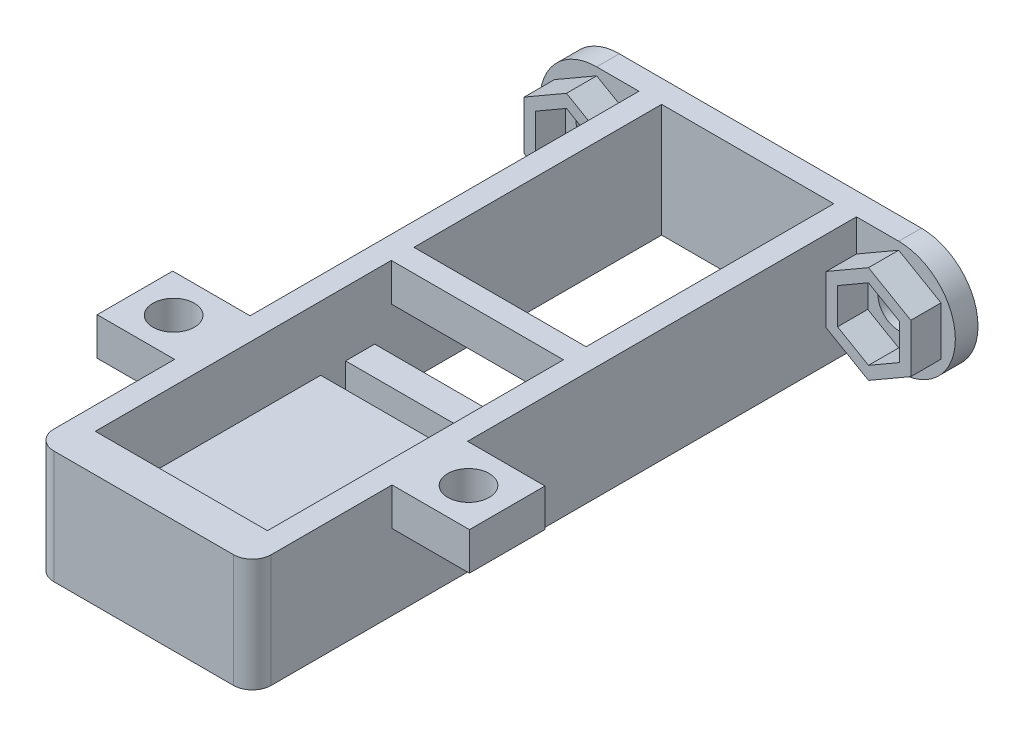
SolidWorks part; units mm, degrees
ref_plane "Front Plane" through (0, 0, 0) normal (0, 0, 1) x (1, 0, 0)
ref_plane "Top Plane" through (0, 0, 0) normal (0, 1, 0) x (1, 0, 0)
ref_plane "Right Plane" through (0, 0, 0) normal (1, 0, 0) x (0, 0, -1)
sketch "Sketch2" plane through (0, 0, 0) normal (0, 0, 1) x (1, 0, 0)
  line L0 (-20, -22.5) -> (20, -22.5)
  line L1 (20, -37.5) -> (-20, -37.5)
  line L3 (12.5, -30) -> (12.5, -22.5)
  circle A0 centre (20, -30) radius 2.75 construction
  circle A1 centre (-20, -30) radius 2.75 construction
  circle A2 centre (20, -30) radius 2.75
  circle A3 centre (-20, -30) radius 2.75
  circle A4 centre (-20, -30) radius 7.5
  circle A5 centre (20, -30) radius 7.5
  circle M2 centre (20, -30) radius 2.75
  circle M15 centre (-20, -30) radius 2.75
  dimension "D1" = 15
  dimension "D2" = 15
extrude "Boss-Extrude1" add sketch "Sketch2" along normal blind 3 contours A4 M15 | A5 L3 L0 A4 L1 | A5 M2 | A5 L0 L3
sketch "Sketch3" plane through (0, 0, 3) normal (0, 0, 1) x (1, 0, 0)
  line L0 (-20, -23.5337) -> (-25.6, -26.7668)
  line L1 (-20, -25.2657) -> (-24.1, -27.6329)
  line L2 (-24.1, -27.6329) -> (-24.1, -32.3671)
  line L3 (-24.1, -32.3671) -> (-20, -34.7343)
  line L4 (-20, -34.7343) -> (-15.9, -32.3671)
  line L5 (-15.9, -32.3671) -> (-15.9, -27.6329)
  line L6 (-15.9, -27.6329) -> (-20, -25.2657)
  line L7 (20, -25.2657) -> (15.9, -27.6329)
  line L8 (15.9, -27.6329) -> (15.9, -32.3671)
  line L9 (15.9, -32.3671) -> (20, -34.7343)
  line L10 (20, -34.7343) -> (24.1, -32.3671)
  line L11 (24.1, -32.3671) -> (24.1, -27.6329)
  line L12 (24.1, -27.6329) -> (20, -25.2657)
  line L13 (-25.6, -26.7668) -> (-25.6, -33.2332)
  line L14 (-25.6, -33.2332) -> (-20, -36.4663)
  line L15 (-20, -36.4663) -> (-14.4, -33.2332)
  line L16 (-14.4, -33.2332) -> (-14.4, -26.7668)
  line L17 (-14.4, -26.7668) -> (-20, -23.5337)
  line L18 (20, -23.5337) -> (14.4, -26.7668)
  line L19 (14.4, -26.7668) -> (14.4, -33.2332)
  line L20 (14.4, -33.2332) -> (20, -36.4663)
  line L21 (20, -36.4663) -> (25.6, -33.2332)
  line L22 (25.6, -33.2332) -> (25.6, -26.7668)
  line L23 (25.6, -26.7668) -> (20, -23.5337)
  circle A0 centre (-20, -30) radius 4.1 construction
  circle A1 centre (20, -30) radius 4.1 construction
  circle A2 centre (-20, -30) radius 5.6
  circle A3 centre (20, -30) radius 5.6
  dimension "D1" = 8.2
  dimension "D2" = 8.2
  dimension "D3" = 1.5
extrude "Boss-Extrude2" add sketch "Sketch3" along normal blind 4 contours A2 L16 L17 | A2 L6 L5 L4 L3 L2 L1 | A2 L17 L0 | A2 L0 L13 | A2 L13 L14 | A2 L14 L15 | A2 L15 L16 | A3 L22 L23 | A3 L12 L11 L10 L9 L8 L7 | A3 L23 L18 | A3 L18 L19 | A3 L19 L20 | A3 L20 L21 | A3 L21 L22
sketch "Sketch4" plane through (0, 0, 3) normal (0, 0, 1) x (1, 0, 0)
  line L0 (-14.4, -26.7668) -> (-14.4, -22.5)
  line L1 (-20, -22.5) -> (20, -22.5) construction
  line L2 (-14.4, -22.5) -> (-11.4, -22.5)
  line L3 (-11.4, -22.5) -> (-11.4, -37.5)
  line L4 (20, -37.5) -> (-20, -37.5) construction
  line L5 (-11.4, -37.5) -> (-14.4, -37.5)
  line L6 (-14.4, -37.5) -> (-14.4, -26.7668)
  line L7 (14.4, -30) -> (14.4, -22.5)
  line L8 (14.4, -26.7668) -> (14.4, -33.2332) construction
  line L9 (14.4, -22.5) -> (11.4, -22.5)
  line L10 (11.4, -22.5) -> (11.4, -37.5)
  line L11 (11.4, -37.5) -> (14.4, -37.5)
  line L12 (14.4, -37.5) -> (14.4, -30)
  dimension "D1" = 3
  dimension "D2" = 3
extrude "Boss-Extrude3" add sketch "Sketch4" along normal blind 80
sketch "Sketch5" plane through (11.4, 0, 0) normal (-1, 0, 0) x (0, 0, 1)
  line L0 (78, -31) -> (48.15, -31)
  line L1 (41, -37.5) -> (44.85, -37.5)
  line L2 (83, -37.5) -> (3, -37.5) construction
  line L3 (78, -37.5) -> (3, -37.5)
  line L4 (41, -31) -> (44.85, -31)
  line L5 (48.15, -37.5) -> (78, -37.5)
  line L6 (41, -31) -> (41, -37.5)
  line L7 (78, -31) -> (78, -37.5)
  line L9 (48.15, -37.5) -> (48.15, -31)
  line L11 (44.85, -37.5) -> (44.85, -31)
  line M6 (3, -37.5) -> (83, -37.5)
extrude "Boss-Extrude4" add sketch "Sketch5" along normal blind 80 contours L9 L3 L7 L0 | L11 L4 L6 M6
sketch "Sketch6" plane through (-68.6, 0, 0) normal (-1, 0, 0) x (0, 0, 1)
  line L4 (48.15, -31) -> (48.15, -37.5)
  line L5 (48.15, -37.5) -> (78, -37.5)
  line L6 (78, -37.5) -> (78, -31)
  line L7 (78, -31) -> (48.15, -31)
  line L8 (48.15, -31) -> (48.15, -37.5)
  line L9 (48.15, -37.5) -> (78, -37.5)
  line L10 (78, -37.5) -> (78, -31)
  line L11 (78, -31) -> (48.15, -31)
  line L12 (41, -37.5) -> (44.85, -37.5)
  line L13 (44.85, -37.5) -> (44.85, -31)
  line L14 (44.85, -31) -> (41, -31)
  line L15 (41, -31) -> (41, -37.5)
  line L16 (41, -37.5) -> (44.85, -37.5)
  line L17 (44.85, -37.5) -> (44.85, -31)
  line L18 (44.85, -31) -> (41, -31)
  line L19 (41, -31) -> (41, -37.5)
  dimension "D1" = 0
  dimension "D2" = 0
extrude "Cut-Extrude1" cut sketch "Sketch6" against normal up to surface (54.2 mm away) up to face at (-14.4, -32.125, 38.5)
sketch "Sketch7" plane through (11.4, 0, 0) normal (-1, 0, 0) x (0, 0, 1)
  line L0 (78, -31) -> (78, -22.5)
  line L1 (83, -22.5) -> (3, -22.5) construction
  line L2 (78, -22.5) -> (83, -22.5)
  line L3 (83, -22.5) -> (83, -37.5)
  line L4 (83, -37.5) -> (78, -37.5)
  line L5 (78, -37.5) -> (78, -31)
extrude "Boss-Extrude5" add sketch "Sketch7" along normal up to surface (22.8 mm away) up to face at (-11.4, -32.8333, 49.6667)
sketch "Sketch8" plane through (0, -22.5, 0) normal (0, -1, 0) x (1, 0, 0)
  line L0 (-10.15, 64.5) -> (-24.65, 64.5) construction
  line L1 (-24.65, 64.5) -> (-24.65, 54.5) construction
  line L2 (-24.65, 54.5) -> (-10.15, 54.5) construction
  line L4 (10.15, 54.5) -> (24.65, 54.5) construction
  line L5 (24.65, 54.5) -> (24.65, 64.5) construction
  line L6 (24.65, 64.5) -> (10.15, 64.5) construction
  line L8 (-14.4, 64.5) -> (-24.65, 64.5)
  line L9 (-24.65, 64.5) -> (-24.65, 54.5)
  line L10 (-24.65, 54.5) -> (-14.4, 54.5)
  line L12 (14.4, 54.5) -> (24.65, 54.5)
  line L13 (24.65, 54.5) -> (24.65, 64.5)
  line L14 (24.65, 64.5) -> (14.4, 64.5)
  line L16 (14.4, 64.5) -> (14.4, 54.5)
  line L17 (14.4, 83) -> (14.4, 3) construction
  line L18 (-14.4, 54.5) -> (-14.4, 64.5)
  line L19 (-14.4, 83) -> (-14.4, 3) construction
  circle A0 centre (19.525, 59.5) radius 2.75 construction
  circle A1 centre (19.525, 59.5) radius 2.75
  circle A2 centre (-19.525, 59.5) radius 2.75 construction
  circle A3 centre (-19.525, 59.5) radius 2.75
extrude "Boss-Extrude6" add sketch "Sketch8" along normal blind 5
sketch "Sketch10" plane through (0, -22.5, 0) normal (0, 1, 0) x (1, 0, 0)
  line L1 (10, -38.8) -> (14.4, -38.8)
  line L2 (10, -38.8) -> (-10, -38.8)
  line L3 (10, -38.8) -> (-10, -38.8)
  line L4 (-10, -38.8) -> (-14.4, -38.8)
  line L5 (14.4, -54.5) -> (14.4, -3) construction
  line L6 (14.4, -38.8) -> (-14.4, -38.8)
  line L8 (14.4, -35.8) -> (-14.4, -35.8)
  line L10 (-14.4, -54.5) -> (-14.4, -3) construction
  line L11 (14.4, -38.8) -> (14.4, -35.8)
  line L12 (-14.4, -54.5) -> (-14.4, -35.8)
  line M3 (11.4, -3) -> (11.4, -78)
  line M5 (-11.4, -78) -> (-11.4, -3)
  dimension "D1" = 0.2
extrude "Boss-Extrude7" add sketch "Sketch10" against normal blind 5 contours L8 L4 L3 L1 M3 M5
fillet "Fillet1" radius 2.5 2 edges at (14.4, -30, 83) (-14.4, -30, 83)
